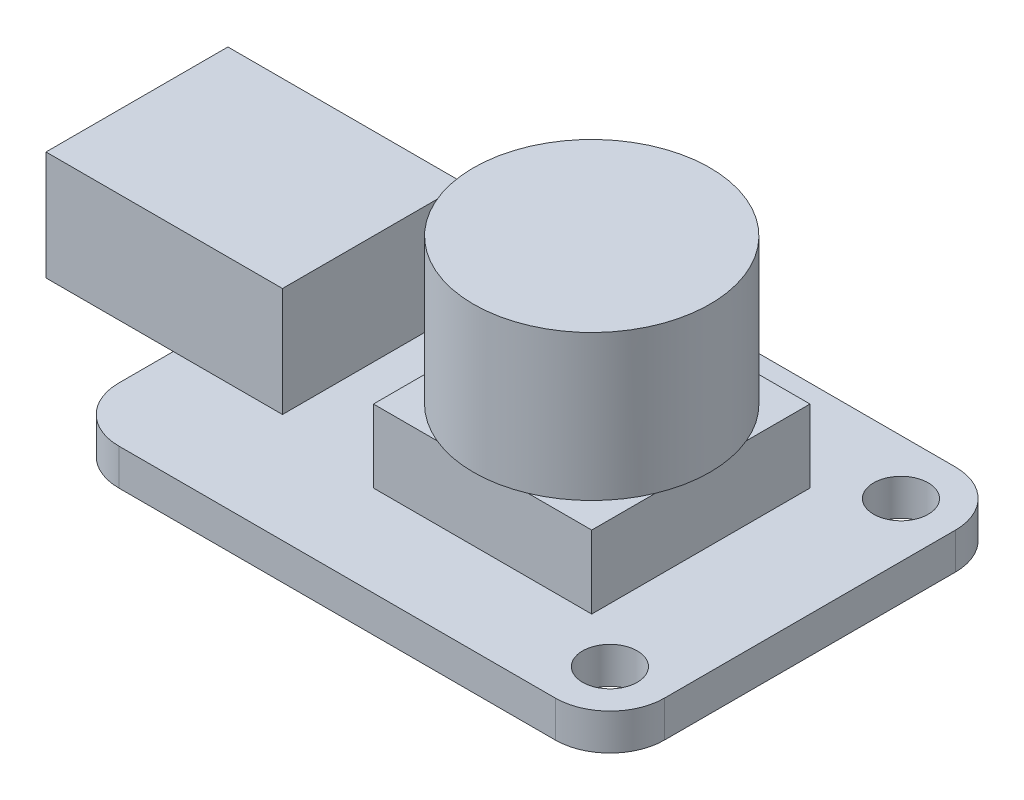
SolidWorks part; units mm, degrees
ref_plane "Front Plane" through (0, 0, 0) normal (0, 0, 1) x (1, 0, 0)
ref_plane "Top Plane" through (0, 0, 0) normal (0, 1, 0) x (1, 0, 0)
ref_plane "Right Plane" through (0, 0, 0) normal (1, 0, 0) x (0, 0, -1)
sketch "Sketch1" plane through (0, 0, 0) normal (0, 1, 0) x (1, 0, 0)
  line L1 (-12, 11) -> (12, 11)
  line L2 (-15, 8) -> (-15, -8)
  line L3 (-12, -11) -> (12, -11)
  line L4 (15, 8) -> (15, -8)
  line L5 (-15, 11) -> (15, -11) construction
  line L6 (-15, -11) -> (15, 11) construction
  circle A0 centre (12, 8) radius 1.5
  circle A1 centre (12, -8) radius 1.5
  arc A2 (15, 8) -> (12, 11) centre (12, 8) ccw
  arc A3 (-15, 8) -> (-12, 11) centre (-12, 8) cw
  arc A4 (-15, -8) -> (-12, -11) centre (-12, -8) ccw
  arc A5 (15, -8) -> (12, -11) centre (12, -8) cw
  point P0 (0, 0)
  dimension "D3" = 3
  dimension "D4" = 3
  dimension "D9" = 3
  dimension "D10" = 3
  dimension "D11" = 3
  dimension "D12" = 3
  dimension "D1" = 30
  dimension "D2" = 22
  dimension "D5" = 3
  dimension "D6" = 3
  dimension "D7" = 3
  dimension "D8" = 3
extrude "Boss-Extrude1" add sketch "Sketch1" along normal blind 2
sketch "Sketch2" plane through (0, 2, 0) normal (0, 1, 0) x (1, 0, 0)
  line L0 (-15, 8) -> (-15, -8) construction
  line L1 (-22, 5) -> (-9, 5)
  line L2 (-22, 5) -> (-22, -5)
  line L3 (-22, -5) -> (-9, -5)
  line L4 (-9, 5) -> (-9, -5)
  line L5 (-22, 5) -> (-9, -5) construction
  line L6 (-22, -5) -> (-9, 5) construction
  point P0 (-15.5, 0)
  point P7 (0, 0)
  dimension "D1" = 10
  dimension "D2" = 13
  dimension "D3" = 6
extrude "Boss-Extrude2" add sketch "Sketch2" along normal blind 6
sketch "Sketch4" plane through (0, 2, 0) normal (0, 1, 0) x (1, 0, 0)
  line L0 (15, -8) -> (15, 8) construction
  line L1 (-3, 6) -> (9, 6)
  line L2 (-3, 6) -> (-3, -6)
  line L3 (-3, -6) -> (9, -6)
  line L4 (9, 6) -> (9, -6)
  line L5 (-3, 6) -> (9, -6) construction
  line L6 (-3, -6) -> (9, 6) construction
  point P0 (3, 0)
  point P5 (0, 0)
  dimension "D1" = 12
  dimension "D2" = 12
  dimension "D3" = 6
extrude "Boss-Extrude4" add sketch "Sketch4" along normal blind 4
sketch "Sketch5" plane through (0, 6, 0) normal (0, 1, 0) x (1, 0, 0)
  line L0 (9, 6) -> (-3, -6) construction
  circle A0 centre (3, 0) radius 6.5
  point P6 (3, 0)
  dimension "D1" = 13
extrude "Boss-Extrude5" add sketch "Sketch5" along normal blind 8
